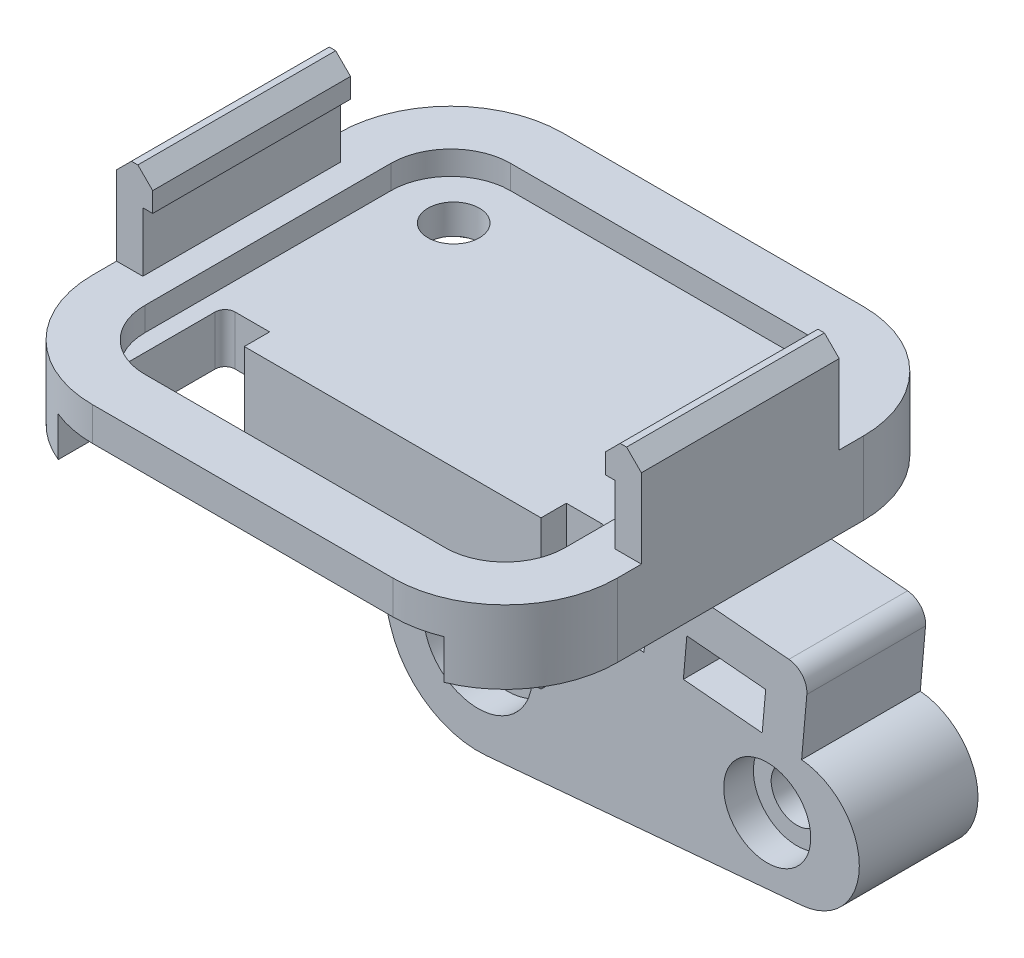
SolidWorks part; units mm, degrees
ref_plane "Front Plane" through (0, 0, 0) normal (0, 0, 1) x (1, 0, 0)
ref_plane "Top Plane" through (0, 0, 0) normal (0, 1, 0) x (1, 0, 0)
ref_plane "Right Plane" through (0, 0, 0) normal (1, 0, 0) x (0, 0, -1)
sketch "Sketch1" plane through (0, -6, 0) normal (0, -1, 0) x (-1, 0, 0)
  line L4 (7.595, 10.65) -> (-7.595, 10.65)
  line L5 (-13.265, 4.98) -> (-13.265, -7.46)
  line L6 (-7.595, -13.13) -> (7.595, -13.13)
  line L7 (13.265, -7.46) -> (13.265, 4.98)
  line L8 (7.595, 10.65) -> (-7.595, 10.65)
  line L9 (-13.265, 4.98) -> (-13.265, -7.46)
  line L10 (-7.595, -13.13) -> (7.595, -13.13)
  line L11 (13.265, -7.46) -> (13.265, 4.98)
  arc A4 (-7.595, 10.65) -> (-13.265, 4.98) centre (-7.595, 4.98) ccw
  arc A5 (-13.265, -7.46) -> (-7.595, -13.13) centre (-7.595, -7.46) ccw
  arc A6 (7.595, -13.13) -> (13.265, -7.46) centre (7.595, -7.46) ccw
  arc A7 (13.265, 4.98) -> (7.595, 10.65) centre (7.595, 4.98) ccw
  arc A8 (-7.595, 10.65) -> (-13.265, 4.98) centre (-7.595, 4.98) ccw
  arc A9 (-13.265, -7.46) -> (-7.595, -13.13) centre (-7.595, -7.46) ccw
  arc A10 (7.595, -13.13) -> (13.265, -7.46) centre (7.595, -7.46) ccw
  arc A11 (13.265, 4.98) -> (7.595, 10.65) centre (7.595, 4.98) ccw
  dimension "D1" = 0
extrude "Boss-Extrude1" add sketch "Sketch1" against normal up to surface (3.7 mm away)
sketch "Sketch3" plane through (0, -2.3, 0) normal (0, 1, 0) x (1, 0, 0)
  line L4 (-7.595, -10.48) -> (7.595, -10.48)
  line L5 (10.615, -7.46) -> (10.615, 4.98)
  line L6 (7.595, 8) -> (-7.595, 8)
  line L7 (-10.615, 4.98) -> (-10.615, -7.46)
  line L8 (-7.595, -10.48) -> (7.595, -10.48)
  line L9 (10.615, -7.46) -> (10.615, 4.98)
  line L10 (7.595, 8) -> (-7.595, 8)
  line L11 (-10.615, 4.98) -> (-10.615, -7.46)
  arc A4 (7.595, -10.48) -> (10.615, -7.46) centre (7.595, -7.46) ccw
  arc A5 (10.615, 4.98) -> (7.595, 8) centre (7.595, 4.98) ccw
  arc A6 (-7.595, 8) -> (-10.615, 4.98) centre (-7.595, 4.98) ccw
  arc A7 (-10.615, -7.46) -> (-7.595, -10.48) centre (-7.595, -7.46) ccw
  arc A8 (7.595, -10.48) -> (10.615, -7.46) centre (7.595, -7.46) ccw
  arc A9 (10.615, 4.98) -> (7.595, 8) centre (7.595, 4.98) ccw
  arc A10 (-7.595, 8) -> (-10.615, 4.98) centre (-7.595, 4.98) ccw
  arc A11 (-10.615, -7.46) -> (-7.595, -10.48) centre (-7.595, -7.46) ccw
  dimension "D1" = 0
extrude "Cut-Extrude1" cut sketch "Sketch3" against normal offset from surface (1.2 mm away) 0.5
sketch "Sketch4" plane through (0, -6, 0) normal (0, 1, 0) x (1, 0, 0)
  line L6 (9.25, -4.27) -> (-9.25, -4.27)
  line L7 (-9.75, -4.77) -> (-9.75, -11.98)
  line L8 (-9.75, -11.98) -> (-9.75, -13.13)
  line L9 (-9.75, -13.13) -> (9.75, -13.13)
  line L10 (9.75, -13.13) -> (9.75, -11.98)
  line L11 (9.75, -11.98) -> (9.75, -4.77)
  line L12 (9.25, -4.27) -> (-9.25, -4.27)
  line L13 (-9.75, -4.77) -> (-9.75, -11.98)
  line L14 (-9.75, -11.98) -> (-9.75, -13.13)
  line L15 (-9.75, -13.13) -> (9.75, -13.13)
  line L16 (9.75, -13.13) -> (9.75, -11.98)
  line L17 (9.75, -11.98) -> (9.75, -4.77)
  arc A2 (-9.25, -4.27) -> (-9.75, -4.77) centre (-9.25, -4.77) ccw
  arc A3 (9.75, -4.77) -> (9.25, -4.27) centre (9.25, -4.77) ccw
  arc A4 (-9.25, -4.27) -> (-9.75, -4.77) centre (-9.25, -4.77) ccw
  arc A5 (9.75, -4.77) -> (9.25, -4.27) centre (9.25, -4.77) ccw
  dimension "D1" = 0
extrude "Cut-Extrude2" cut sketch "Sketch4" along normal offset from surface (2 mm away) 1
sketch "Sketch5" plane through (0, -2.3, 0) normal (0, 1, 0) x (1, 0, 0)
  line L4 (-9.25, -9.63) -> (9.25, -9.63)
  line L5 (-9.75, -4.77) -> (-9.75, -9.13)
  line L6 (9.25, -4.27) -> (-9.25, -4.27)
  line L7 (9.75, -9.13) -> (9.75, -4.77)
  line L8 (-9.25, -9.63) -> (9.25, -9.63)
  line L9 (-9.75, -4.77) -> (-9.75, -9.13)
  line L10 (9.25, -4.27) -> (-9.25, -4.27)
  line L11 (9.75, -9.13) -> (9.75, -4.77)
  arc A4 (-9.75, -9.13) -> (-9.25, -9.63) centre (-9.25, -9.13) ccw
  arc A5 (-9.25, -4.27) -> (-9.75, -4.77) centre (-9.25, -4.77) ccw
  arc A6 (9.75, -4.77) -> (9.25, -4.27) centre (9.25, -4.77) ccw
  arc A7 (9.25, -9.63) -> (9.75, -9.13) centre (9.25, -9.13) ccw
  arc A8 (-9.75, -9.13) -> (-9.25, -9.63) centre (-9.25, -9.13) ccw
  arc A9 (-9.25, -4.27) -> (-9.75, -4.77) centre (-9.25, -4.77) ccw
  arc A10 (9.75, -4.77) -> (9.25, -4.27) centre (9.25, -4.77) ccw
  arc A11 (9.25, -9.63) -> (9.75, -9.13) centre (9.25, -9.13) ccw
  dimension "D1" = 0
extrude "Cut-Extrude3" cut sketch "Sketch5" against normal through all
sketch "Sketch6" plane through (0, 0, 1.24) normal (0, 0, -1) x (-1, 0, 0)
  line L5 (-11.94, -2.3) -> (-11.94, 0.7)
  line L6 (-11.94, 0.7) -> (-11.44, 0.7)
  line L7 (-11.44, 0.7) -> (-11.44, 1.7)
  line L8 (-11.44, 1.7) -> (-12.19, 2.45)
  line L9 (-12.19, 2.45) -> (-13.265, 2.45)
  line L10 (-13.265, 2.45) -> (-13.265, -2.3)
  line L11 (-13.265, -2.3) -> (-11.94, -2.3)
  dimension "D1" = 135
  dimension "D2" = 0.75
extrude "Boss-Extrude3" add sketch "Sketch6" along normal mid plane 10
mirror "Mirror1" about plane through (0, 0, 0) normal (1, 0, 0) of "Boss-Extrude3"
hole_wizard "M2 Clearance Hole1" positions "Sketch7" profile "Sketch8" hole size "M2" standard "ANSI Metric"
sketch "Sketch7" plane through (0, -3.5, 0) normal (0, 1, 0) x (1, 0, 0)
  point P0 (-7.615, 5.15)
  point P2 (7.615, 5.15)
sketch "Sketch8" plane through (-7.615, -3.5, -5.15) normal (1, 0, 0) x (0, 0, 1)
  line L0 (0, 0) -> (0, 2.5)
  line L1 (0, 2.5) -> (1.3, 2.5)
  line L2 (1.3, 2.5) -> (1.3, 0)
  line L5 (1.3, 0) -> (0, 0)
  line L11 (0, -6.35) -> (0, 107.95) construction
  dimension "Thru Hole Dia." = 2.6
  dimension "Thru Hole Depth" = 2.5
sketch "Sketch9" plane through (0, -6, 0) normal (0, -1, 0) x (1, 0, 0)
  line L1 (-7.615, -2.6674) -> (-9.765, -3.9087)
  line L2 (-9.765, -3.9087) -> (-9.765, -6.3913)
  line L3 (-9.765, -6.3913) -> (-7.615, -7.6326)
  line L4 (-7.615, -7.6326) -> (-5.465, -6.3913)
  line L5 (-5.465, -6.3913) -> (-5.465, -3.9087)
  line L6 (-5.465, -3.9087) -> (-7.615, -2.6674)
  line L7 (7.615, -2.6674) -> (5.465, -3.9087)
  line L8 (5.465, -3.9087) -> (5.465, -6.3913)
  line L9 (5.465, -6.3913) -> (7.615, -7.6326)
  line L10 (7.615, -7.6326) -> (9.765, -6.3913)
  line L11 (9.765, -6.3913) -> (9.765, -3.9087)
  line L12 (9.765, -3.9087) -> (7.615, -2.6674)
  circle A0 centre (-7.615, -5.15) radius 2 construction
  circle A1 centre (-7.615, -5.15) radius 2.15 construction
  circle A2 centre (7.615, -5.15) radius 2.15 construction
  dimension "D1" = 4
  dimension "D2" = 0.15
extrude "Cut-Extrude4" cut sketch "Sketch9" against normal blind 1
chamfer "Chamfer2" distance 0.75 angle 45
sketch "Sketch11" plane through (0, 0, -1.76) normal (0, 0, -1) x (-1, 0, 0)
  line L1 (-16.3626, -18.1875) -> (-0.408, -19.602)
  line L2 (-0.302, -11.5934) -> (-16.2566, -13.0078)
  line L3 (-16.2566, -16.9922) -> (-0.302, -18.4066)
  line L4 (-0.302, -11.5934) -> (-16.2566, -13.0078) construction
  line L5 (-16.2566, -16.9922) -> (-0.302, -18.4066) construction
  line L6 (7.595, -6) -> (4.4167, -16.3556)
  line L7 (-16.3626, -11.8125) -> (-7.595, -11.0352)
  line L9 (-0.408, -10.398) -> (-16.3626, -11.8125) construction
  line L10 (-7.595, -2.3) -> (-7.595, -6) construction
  line L12 (-7.595, -3.5) -> (-7.595, -11.0352)
  line L13 (7.595, -3.5) -> (7.595, -6)
  line L14 (7.595, -3.5) -> (-7.595, -3.5)
  line L15 (7.595, -2.3) -> (7.595, -6) construction
  line L16 (-7.595, -3.5) -> (7.595, -3.5) construction
  arc A2 (-16.3626, -11.8125) -> (-16.3626, -18.1875) centre (-16.08, -15) ccw
  arc A3 (-0.408, -19.602) -> (4.4167, -16.3556) centre (0, -15) ccw
  arc A4 (-0.302, -18.4066) -> (-0.302, -11.5934) centre (0, -15) ccw
  arc A5 (-16.2566, -13.0078) -> (-16.2566, -16.9922) centre (-16.08, -15) ccw
  arc A6 (-0.302, -18.4066) -> (-0.302, -11.5934) centre (0, -15) ccw construction
  arc A7 (-16.2566, -13.0078) -> (-16.2566, -16.9922) centre (-16.08, -15) ccw construction
  arc A8 (-0.408, -19.602) -> (-0.408, -10.398) centre (0, -15) ccw construction
  arc A9 (-16.3626, -11.8125) -> (-16.3626, -18.1875) centre (-16.08, -15) ccw construction
  dimension "D1" = 0
  dimension "D2" = 1.2
extrude "Boss-Extrude4" add sketch "Sketch11" against normal blind 3
sketch "Sketch12" plane through (0, 0, -1.76) normal (0, 0, -1) x (-1, 0, 0)
  line L0 (-0.408, -10.398) -> (-16.3626, -11.8125)
  line L1 (-16.3626, -18.1875) -> (-0.408, -19.602)
  line L2 (-0.302, -11.5934) -> (-16.2566, -13.0078)
  line L3 (-16.2566, -16.9922) -> (-0.302, -18.4066)
  line L4 (-0.302, -11.5934) -> (-16.2566, -13.0078) construction
  line L5 (-16.2566, -16.9922) -> (-0.302, -18.4066) construction
  arc A0 (-16.3626, -11.8125) -> (-16.3626, -18.1875) centre (-16.08, -15) ccw
  arc A1 (-0.408, -19.602) -> (-0.408, -10.398) centre (0, -15) ccw
  arc A2 (-0.302, -18.4066) -> (-0.302, -11.5934) centre (0, -15) ccw
  arc A3 (-16.2566, -13.0078) -> (-16.2566, -16.9922) centre (-16.08, -15) ccw
  arc A4 (-0.302, -18.4066) -> (-0.302, -11.5934) centre (0, -15) ccw construction
  arc A5 (-16.2566, -13.0078) -> (-16.2566, -16.9922) centre (-16.08, -15) ccw construction
  arc A6 (-16.3626, -11.8125) -> (-16.3626, -18.1875) centre (-16.08, -15) ccw construction
  dimension "D1" = 0
extrude "Boss-Extrude5" add sketch "Sketch12" along normal blind 3
hole_wizard "CBORE for M2.5 SHCS1" positions "Sketch15" profile "Sketch16" counterbore size "M2.5" standard "ANSI Metric"
sketch "Sketch15" plane through (0, 0, 1.24) normal (0, 0, 1) x (1, 0, 0)
  point P0 (0, -15)
sketch "Sketch16" plane through (0, -15, 1.24) normal (1, 0, 0) x (0, -1, 0)
  line L0 (0, 0) -> (0, 11.89)
  line L1 (0, 11.89) -> (1.55, 11.89)
  line L3 (1.55, 11.89) -> (1.55, 1.5)
  line L4 (1.55, 1.5) -> (2.75, 1.5)
  line L5 (2.75, 1.5) -> (2.75, 0)
  line L7 (2.75, 0) -> (0, 0)
  line L11 (0, -6.35) -> (0, 107.95) construction
  dimension "Thru Hole Dia." = 3.1
  dimension "Thru Hole Depth" = 11.89
  dimension "C'Bore Dia." = 5.5
  dimension "C'Bore Depth" = 1.5
sketch "Sketch17" plane through (0, 0, -4.76) normal (0, 0, -1) x (-1, 0, 0)
  line L0 (-0.3197, -11.3941) -> (-16.2743, -12.8086)
  line L1 (-16.2743, -17.1914) -> (-0.3197, -18.6059)
  line L2 (-0.302, -11.5934) -> (-16.2566, -13.0078)
  line L3 (-16.2566, -16.9922) -> (-0.302, -18.4066)
  line L4 (-0.302, -11.5934) -> (-16.2566, -13.0078) construction
  line L5 (-16.2566, -16.9922) -> (-0.302, -18.4066) construction
  arc A0 (-16.2743, -12.8086) -> (-16.2743, -17.1914) centre (-16.08, -15) ccw
  arc A1 (-0.3197, -18.6059) -> (-0.3197, -11.3941) centre (0, -15) ccw
  arc A2 (-0.302, -18.4066) -> (-0.302, -11.5934) centre (0, -15) ccw
  arc A3 (-16.2566, -13.0078) -> (-16.2566, -16.9922) centre (-16.08, -15) ccw
  arc A4 (-0.302, -18.4066) -> (-0.302, -11.5934) centre (0, -15) ccw construction
  arc A5 (-16.2566, -13.0078) -> (-16.2566, -16.9922) centre (-16.08, -15) ccw construction
  dimension "D1" = 0
  dimension "D2" = 0.2
extrude "Cut-Extrude6" cut sketch "Sketch17" against normal blind 2.5
sketch "Sketch18" plane through (0, 0, -2.26) normal (0, 0, -1) x (-1, 0, 0)
  circle A0 centre (0, -15) radius 3.62
  arc A1 (-0.3197, -18.6059) -> (-0.3197, -11.3941) centre (0, -15) ccw construction
extrude "Cut-Extrude7" cut sketch "Sketch18" against normal blind 1
hole_wizard "CBORE for M2 SHCS1" positions "Sketch19" profile "Sketch20" counterbore size "M2" standard "ANSI Metric"
sketch "Sketch19" plane through (0, 0, 1.24) normal (0, 0, 1) x (1, 0, 0)
  point P0 (14.625, -15)
sketch "Sketch20" plane through (14.625, -15, 1.24) normal (1, 0, 0) x (0, -1, 0)
  line L0 (0, 0) -> (0, 11.89)
  line L1 (0, 11.89) -> (1.3, 11.89)
  line L3 (1.3, 11.89) -> (1.3, 1.5)
  line L4 (1.3, 1.5) -> (2.2, 1.5)
  line L5 (2.2, 1.5) -> (2.2, 0)
  line L7 (2.2, 0) -> (0, 0)
  line L11 (0, -6.35) -> (0, 107.95) construction
  dimension "Thru Hole Dia." = 2.6
  dimension "Thru Hole Depth" = 11.89
  dimension "C'Bore Dia." = 4.4
  dimension "C'Bore Depth" = 1.5
sketch "Sketch21" plane through (0, 0, 1.24) normal (0, 0, 1) x (1, 0, 0)
  line L2 (8.3853, -18.8947) -> (8.3853, -24.9183) construction
  line L4 (-3.6365, -17.8495) -> (1.6539, -24.6012)
  line L5 (3.4048, -25.3598) -> (13.3658, -24.4767)
  line L6 (14.926, -23.4761) -> (18.8591, -16.5865)
  line L7 (16.3626, -18.1875) -> (0.408, -19.602) construction
  line L8 (16.3626, -18.1875) -> (0.408, -19.602)
  arc A6 (-4.4167, -16.3556) -> (0.408, -19.602) centre (0, -15) ccw construction
  arc A7 (1.6539, -24.6012) -> (3.4048, -25.3598) centre (3.2282, -23.3676) ccw
  arc A8 (13.3658, -24.4767) -> (14.926, -23.4761) centre (13.1891, -22.4845) ccw
  arc A9 (16.3626, -18.1875) -> (16.3626, -11.8125) centre (16.08, -15) ccw construction
  arc A10 (16.3626, -18.1875) -> (18.8591, -16.5865) centre (16.08, -15) ccw
  arc A11 (-3.6365, -17.8495) -> (0.408, -19.602) centre (0, -15) ccw
  dimension "D1" = 10
  dimension "D3" = 2
  dimension "D2" = 6
extrude "Boss-Extrude6" [suppressed] add sketch "Sketch21" against normal blind 3
ref_plane "Plane1" [suppressed] through (0, 0, -0.76) normal (0, 0, 1) x (1, 0, 0)
sketch "Sketch22" [suppressed] plane through (0, 0, -0.76) normal (0, 0, 1) x (1, 0, 0)
  line L2 (-3.6365, -17.8495) -> (1.6539, -24.6012)
  line L3 (-3.6365, -17.8495) -> (1.6539, -24.6012)
  line L8 (3.4048, -25.3598) -> (13.3658, -24.4767)
  line L9 (3.4048, -25.3598) -> (13.3658, -24.4767)
  line L10 (14.926, -23.4761) -> (18.8591, -16.5865)
  line L11 (14.926, -23.4761) -> (18.8591, -16.5865)
  line L12 (16.3626, -18.1875) -> (0.408, -19.602)
  line L13 (16.3626, -18.1875) -> (0.408, -19.602)
  arc A4 (1.6539, -24.6012) -> (3.4048, -25.3598) centre (3.2282, -23.3676) ccw
  arc A5 (1.6539, -24.6012) -> (3.4048, -25.3598) centre (3.2282, -23.3676) ccw
  arc A6 (13.3658, -24.4767) -> (14.926, -23.4761) centre (13.1891, -22.4845) ccw
  arc A7 (13.3658, -24.4767) -> (14.926, -23.4761) centre (13.1891, -22.4845) ccw
  arc A12 (16.3626, -18.1875) -> (18.8591, -16.5865) centre (16.08, -15) ccw
  arc A13 (16.3626, -18.1875) -> (18.8591, -16.5865) centre (16.08, -15) ccw
  arc A14 (-3.6365, -17.8495) -> (0.408, -19.602) centre (0, -15) ccw
  arc A15 (-3.6365, -17.8495) -> (0.408, -19.602) centre (0, -15) ccw
  dimension "D1" = 0
extrude "Cut-Extrude8" [suppressed] cut sketch "Sketch22" against normal mid plane 1
hole_wizard "M2 Clearance Hole2" [suppressed] positions "Sketch23" profile "Sketch24" hole size "M2" standard "ANSI Metric"
sketch "Sketch23" [suppressed] plane through (0, 0, -2.26) normal (0, 0, -1) x (-1, 0, 0)
  point P0 (-13.1891, -22.4845)
  point P3 (-3.2282, -23.3676)
sketch "Sketch24" plane through (13.1891, -22.4845, -2.26) normal (1, 0, 0) x (0, 1, 0)
  line L0 (0, 0) -> (0, 15.39)
  line L1 (0, 15.39) -> (1.2, 15.39)
  line L2 (1.2, 15.39) -> (1.2, 0)
  line L5 (1.2, 0) -> (0, 0)
  line L11 (0, -6.35) -> (0, 107.95) construction
  dimension "Thru Hole Dia." = 2.4
  dimension "Thru Hole Depth" = 15.39
sketch "Sketch28" [suppressed] plane through (0, 0, -2.26) normal (0, 0, -1) x (-1, 0, 0)
  line L0 (-6.8911, -25.0507) -> (-9.8794, -24.7858)
  line L1 (-6.8911, -25.0507) -> (-6.3613, -19.0742)
  line L2 (-9.8794, -24.7858) -> (-9.3496, -18.8092)
  line L3 (-6.3613, -19.0742) -> (-9.3496, -18.8092)
  line L4 (-3.4048, -25.3598) -> (-13.3658, -24.4767) construction
  line L5 (-16.3626, -18.1875) -> (-0.408, -19.602) construction
  point P4 (-8.3853, -24.9183)
  dimension "D1" = 3
extrude "Boss-Extrude7" [suppressed] add sketch "Sketch28" along normal up to surface (2.5 mm away)
sketch "Sketch29" [suppressed] plane through (7.6221, 0.6757, 0) normal (0.9961, 0.0883, 0) x (0, 0, -1)
  line L0 (4.76, -25.5614) -> (2.26, -25.5614)
  line L1 (2.26, -25.5614) -> (4.76, -19.5614)
  line L2 (4.76, -19.5614) -> (4.76, -25.5614)
extrude "Cut-Extrude9" [suppressed] cut sketch "Sketch29" against normal through all
chamfer "Chamfer3" distance 0.5 angle 45
sketch "Sketch30" plane through (0, 0, 0) normal (1, 0, 0) x (0, 0, -1)
  line L0 (-5.55, -7.7) -> (-6.4, -9.05)
  line L1 (-5.55, -3.5) -> (-3.77, -3.5)
  line L2 (-5.55, -3.5) -> (-5.55, -7.7)
  line L3 (-5.55, -11) -> (-3.77, -11)
  line L4 (-3.77, -3.5) -> (-3.77, -11)
  line L5 (-6.4, -9.05) -> (-6.4, -10.15)
  line L6 (-6.4, -10.15) -> (-5.55, -11)
  line L7 (-5.55, -11) -> (-5.55, -7.7) construction
  line L8 (-6.4, -9.6) -> (-6.2637, -9.6) construction
  line L9 (-6.2637, -9.6) -> (-4.7, -9.6) construction
  line L10 (-6.6, -18.47) -> (-6.6, -7.7) construction
  point P7 (-4.27, -3.5)
  dimension "D1" = 1.7
  dimension "D2" = 0.85
  dimension "D3" = 0.2
  dimension "D4" = 3.3
  dimension "D5" = 1.1
  dimension "D6" = 45
  dimension "D7" = 4.2
  dimension "D8" = 0.5
extrude "Boss-Extrude8" add sketch "Sketch30" along normal mid plane 15
sketch "Sketch31" plane through (0, 0, 1.24) normal (0, 0, 1) x (1, 0, 0)
  line L0 (8.3938, -11.106) -> (10.386, -11.2827)
  line L1 (8.3938, -11.106) -> (8.7471, -7.1217)
  line L2 (10.386, -11.2827) -> (10.5626, -9.2905)
  line L4 (7.595, -11.0352) -> (16.3626, -11.8125) construction
  line L5 (14.3704, -11.6359) -> (16.3626, -11.8125)
  line L6 (14.3704, -11.6359) -> (14.547, -9.6437)
  line L7 (16.3626, -11.8125) -> (16.7158, -7.8281)
  line L18 (8.7471, -7.1217) -> (16.7158, -7.8281)
  line L19 (10.5626, -9.2905) -> (14.547, -9.6437)
  arc A0 (16.3626, -18.1875) -> (16.3626, -11.8125) centre (16.08, -15) ccw construction
  dimension "D1" = 4
  dimension "D2" = 2
  dimension "D3" = 2
  dimension "D4" = 2
extrude "Boss-Extrude9" add sketch "Sketch31" against normal up to surface (6 mm away)
fillet "Fillet1" radius 1
